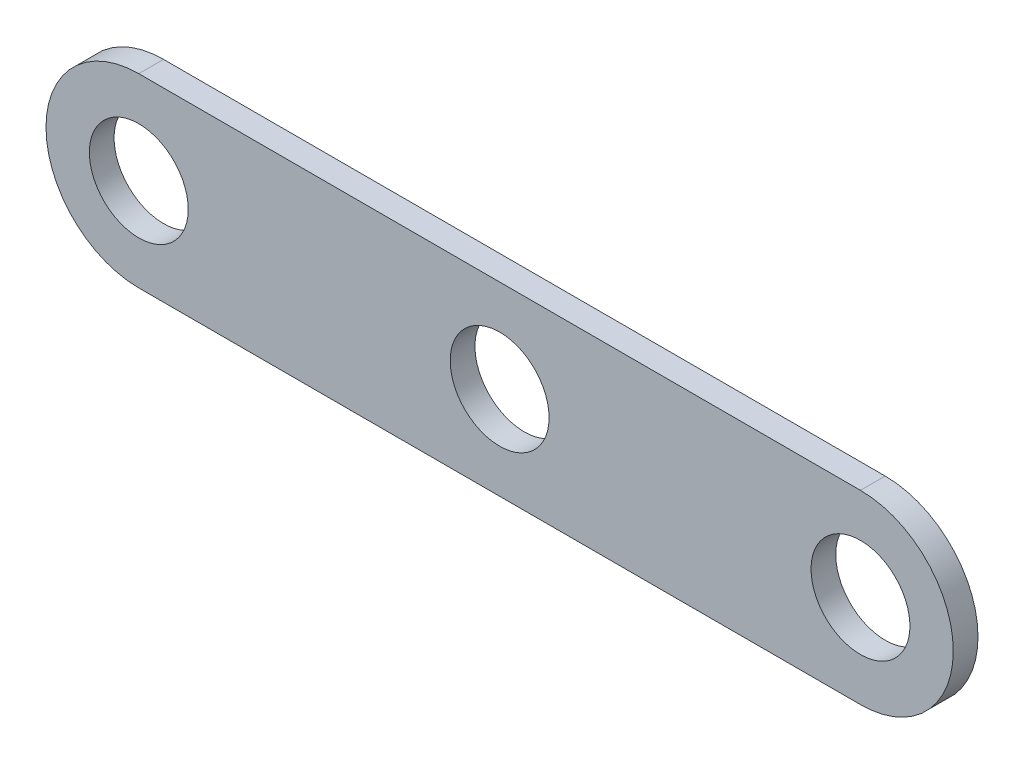
SolidWorks part; units mm, degrees
ref_plane "Front Plane" through (0, 0, 0) normal (0, 0, 1) x (1, 0, 0)
ref_plane "Top Plane" through (0, 0, 0) normal (0, 1, 0) x (1, 0, 0)
ref_plane "Right Plane" through (0, 0, 0) normal (1, 0, 0) x (0, 0, -1)
sketch "Sketch2" plane through (0, 0, 0) normal (0, 0, 1) x (1, 0, 0)
  line L0 (0, 22.5) -> (0, -22.5) construction
  line L1 (-87.5, -22.5) -> (87.5, -22.5)
  line L3 (-87.5, 22.5) -> (87.5, 22.5)
  line L5 (-87.5, -22.5) -> (87.5, 22.5) construction
  line L6 (-87.5, 22.5) -> (87.5, -22.5) construction
  arc A0 (87.5, -22.5) -> (87.5, 22.5) centre (87.5, 0) ccw
  arc A1 (-87.5, -22.5) -> (-87.5, 22.5) centre (-87.5, 0) cw
  circle A2 centre (-87.5, 0) radius 11.99
  circle A4 centre (87.5, 0) radius 11.99
  circle A5 centre (0, 0) radius 11.99
  point P0 (0, 0)
  dimension "D3" = 23.98
  dimension "D4" = 23.98
  dimension "D1" = 45
  dimension "D2" = 175
extrude "Boss-Extrude1" add sketch "Sketch2" along normal blind 6
